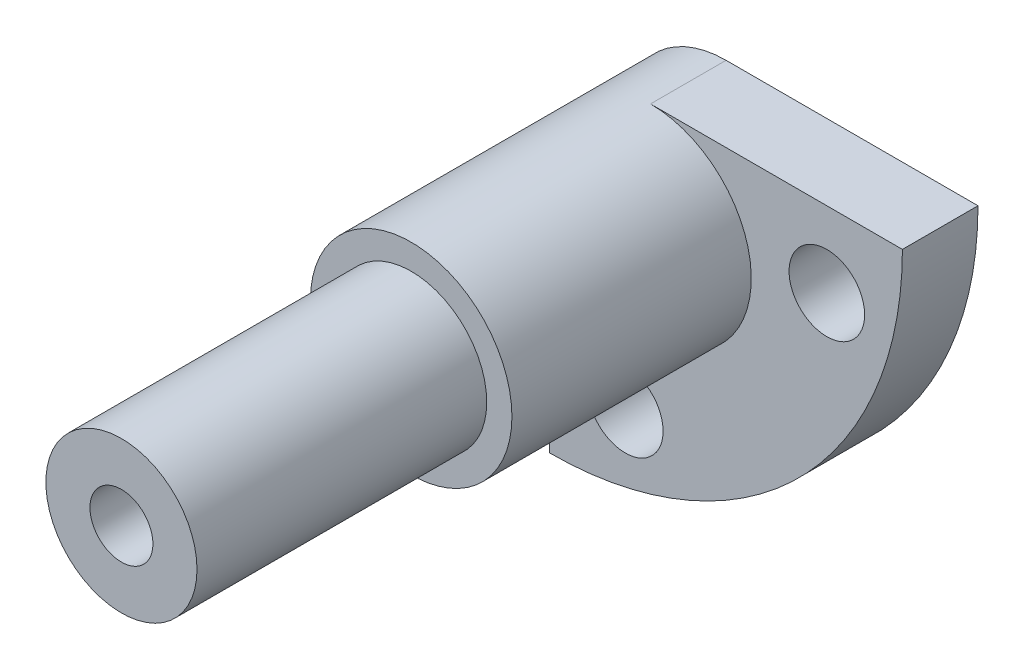
SolidWorks part; units mm, degrees
material "AISI 1020"
ref_plane "Front" through (0, 0, 0) normal (0, 0, 1) x (1, 0, 0)
ref_plane "Top" through (0, 0, 0) normal (0, 1, 0) x (1, 0, 0)
ref_plane "Right" through (0, 0, 0) normal (1, 0, 0) x (0, 0, -1)
sketch "Sketch1" plane through (0, 0, 0) normal (0, 0, 1) x (1, 0, 0)
  line L1 (10, 4) -> (0, 4)
  line L2 (-4, 0) -> (-4, -10)
  arc A0 (0, 4) -> (-4, 0) centre (0, 0) ccw
  arc A1 (10, 4) -> (-4, -10) centre (-4, 4) cw
  dimension "D1" = 4
  dimension "D2" = 14
  dimension "D3" = 10
  dimension "D4" = 10
extrude "Extrude1" add sketch "Sketch1" along normal blind 3
sketch "Sketch2" plane through (0, 0, 3) normal (0, 0, 1) x (1, 0, 0)
  circle A0 centre (0, 0) radius 4
extrude "Extrude2" add sketch "Sketch2" along normal blind 9.5
sketch "Sketch3" plane through (0, 0, 12.5) normal (0, 0, 1) x (1, 0, 0)
  circle A0 centre (0, 0) radius 3
  dimension "D1" = 6
extrude "Extrude3" add sketch "Sketch3" along normal blind 11.5
sketch "Sketch4" plane through (0, 0, 24) normal (0, 0, 1) x (1, 0, 0)
  circle A0 centre (0, 0) radius 1.25
  dimension "D1" = 2.5
extrude "Extrude4" cut sketch "Sketch4" against normal blind 10
cosmetic thread "Hole Thread1" parameters "D1"=6, "D2"=3
sketch "Sketch5" plane through (0, 0, 3) normal (0, 0, 1) x (1, 0, 0)
  line L0 (10, 4) -> (0, 4) construction
  line L2 (-4, 0) -> (-4, -10) construction
  circle A0 centre (7, 1) radius 1.5
  circle A1 centre (-1, -7) radius 1.5
  dimension "D1" = 3
  dimension "D3" = 3
  dimension "D2" = 3
  dimension "D4" = 3
  dimension "D5" = 3
  dimension "D6" = 3
extrude "Extrude5" cut sketch "Sketch5" against normal up to surface (3 mm away) up to face at (1.0178, -1.0178, 0)
hole_wizard "M3 Tapped Hole1" positions "3DSketch1" profile "Sketch6" tap size "M3" standard "DIN"
sketch3d "3DSketch1"
  line L0 (0, 0, 14) -> (0, 0, 24) construction
  point P0 (0, 0, 24)
sketch "Sketch6" plane through (0, 0, 24) normal (1, 0, 0) x (0, -1, 0)
  line L0 (0, 0) -> (0, 8.2511)
  line L1 (0, 8.2511) -> (1.25, 7.5)
  line L2 (1.25, 7.5) -> (1.25, 0)
  line L5 (1.25, 0) -> (0, 0)
  line L10 (0, 8.2511) -> (-1.25, 7.5) construction
  line L11 (0, -6.35) -> (0, 107.95) construction
  dimension "Tap Drill Dia." = 2.5
  dimension "Tap Drill Depth" = 7.5
  dimension "Drill Angle" = 118
